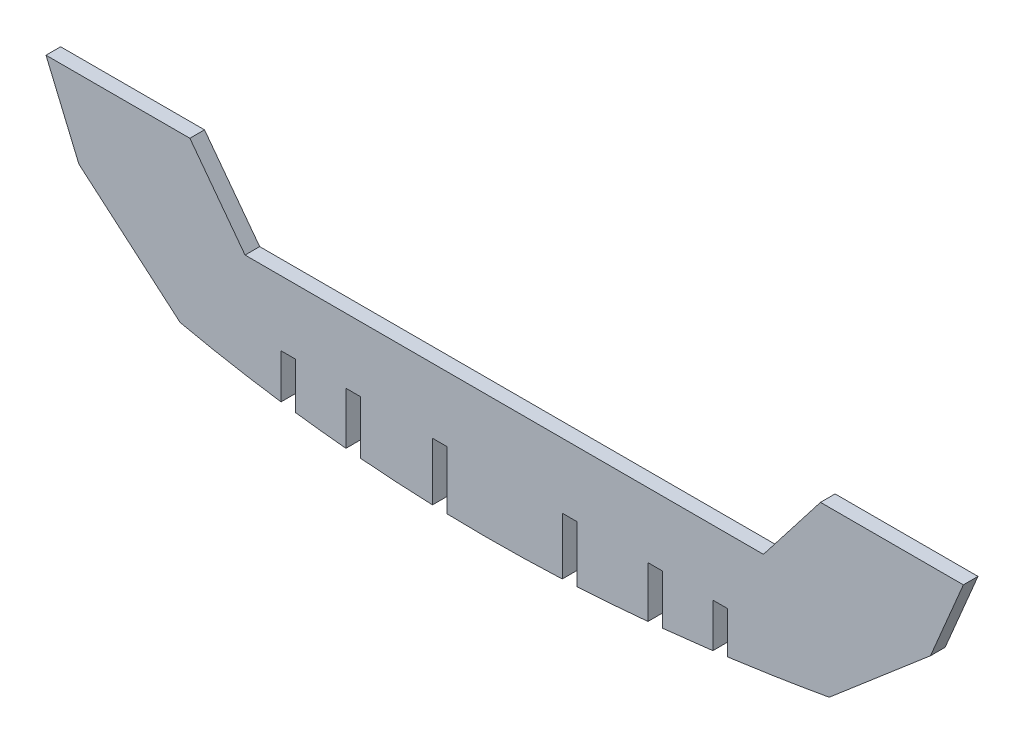
SolidWorks part; units mm, degrees
ref_plane "Front Plane" through (0, 0, 0) normal (0, 0, 1) x (1, 0, 0)
ref_plane "Top Plane" through (0, 0, 0) normal (0, 1, 0) x (1, 0, 0)
ref_plane "Right Plane" through (0, 0, 0) normal (1, 0, 0) x (0, 0, -1)
sketch "Sketch1" plane through (0, 0, 0) normal (0, 0, 1) x (1, 0, 0)
  line L0 (-76.2, 19.05) -> (-83.82, 29.21)
  line L1 (-83.82, 29.21) -> (-134.62, 29.21)
  line L2 (-76.2, -19.05) -> (-95.25, -19.05)
  line L3 (-76.2, 19.05) -> (76.2, 19.05)
  line L4 (-76.2, 19.05) -> (-76.2, -19.05)
  line L5 (-76.2, -19.05) -> (76.2, -19.05)
  line L6 (76.2, 19.05) -> (76.2, -19.05)
  line L7 (-76.2, 19.05) -> (76.2, -19.05) construction
  line L8 (-76.2, -19.05) -> (76.2, 19.05) construction
  line L9 (-95.25, -19.05) -> (-124.968, 6.35)
  line L10 (76.2, 19.05) -> (83.82, 29.21)
  line L11 (83.82, 29.21) -> (134.62, 29.21)
  line L12 (134.62, 29.21) -> (124.968, 6.35)
  line L13 (124.968, 6.35) -> (95.25, -19.05)
  line L14 (95.25, -19.05) -> (76.2, -19.05)
  spline S0 degree 1 poles (-134.62, 29.21) (-124.968, 6.35) knots 0 0 1 1
  spline S1 degree 3 poles (-95.25, -19.05) (-66.0792, -25.5147) (-2.1216, -32.0837) (61.7619, -25.0102) (95.25, -19.05) knots 0 0 0 0 0.467199 1 1 1 1
  point P4 (0, 0)
  dimension "D1" = 152.4
  dimension "D2" = 38.1
  dimension "D3" = 12.7
  dimension "D4" = 50.8
  dimension "D5" = 12.7
  dimension "D6" = 19.05
  dimension "D7" = 19.05
  dimension "D8" = 50.8
  dimension "D9" = 48.26
  dimension "D10" = 48.26
  dimension "D11" = 25.4
  dimension "D12" = 48.768
  dimension "D13" = 48.768
extrude "Boss-Extrude1" add sketch "Sketch1" along normal blind 4.2926 contours L1 S0 L9 L2 L4 L0 | L6 L3 L4 L5 | L2 S1 L14 L5 | L14 L13 L12 L11 L10 L6
sketch "Sketch2" plane through (0, 0, 4.2926) normal (0, 0, 1) x (1, 0, 0)
  line L1 (-76.2, 19.05) -> (75.9425, 19.05)
  line L2 (-76.2, 19.05) -> (-76.2, 7.62)
  line L3 (-76.2, 7.62) -> (75.9425, 7.62)
  line L4 (75.9425, 19.05) -> (75.9425, 7.62)
  dimension "D1" = 11.43
extrude "Cut-Extrude1" cut sketch "Sketch2" against normal blind 4.2926
sketch "Sketch3" plane through (0, 0, 4.2926) normal (0, 0, 1) x (1, 0, 0)
  line L1 (-65.6463, -31.75) -> (-61.3537, -31.75)
  line L2 (-65.6463, -31.75) -> (-65.6463, -11.43)
  line L3 (-65.6463, -11.43) -> (-61.3537, -11.43)
  line L4 (-61.3537, -31.75) -> (-61.3537, -11.43)
  line L5 (-65.6463, -31.75) -> (-61.3537, -11.43) construction
  line L6 (-65.6463, -11.43) -> (-61.3537, -31.75) construction
  line L7 (-46.5963, -31.75) -> (-42.3037, -31.75)
  line L8 (-46.5963, -31.75) -> (-46.5963, -11.43)
  line L9 (-46.5963, -11.43) -> (-42.3037, -11.43)
  line L10 (-42.3037, -31.75) -> (-42.3037, -11.43)
  line L11 (-46.5963, -31.75) -> (-42.3037, -11.43) construction
  line L12 (-46.5963, -11.43) -> (-42.3037, -31.75) construction
  line L13 (-21.1963, -11.43) -> (-16.9037, -11.43)
  line L14 (-21.1963, -11.43) -> (-21.1963, -31.75)
  line L15 (-21.1963, -31.75) -> (-16.9037, -31.75)
  line L16 (-16.9037, -11.43) -> (-16.9037, -31.75)
  line L17 (-21.1963, -11.43) -> (-16.9037, -31.75) construction
  line L18 (-21.1963, -31.75) -> (-16.9037, -11.43) construction
  line L19 (42.0462, -11.43) -> (46.3388, -11.43)
  line L20 (42.0462, -11.43) -> (42.0462, -31.75)
  line L21 (42.0462, -31.75) -> (46.3388, -31.75)
  line L22 (46.3388, -11.43) -> (46.3388, -31.75)
  line L23 (42.0462, -11.43) -> (46.3388, -31.75) construction
  line L24 (42.0462, -31.75) -> (46.3388, -11.43) construction
  line L25 (61.0962, -11.43) -> (65.3888, -11.43)
  line L26 (61.0962, -11.43) -> (61.0962, -31.75)
  line L27 (61.0962, -31.75) -> (65.3888, -31.75)
  line L28 (65.3888, -11.43) -> (65.3888, -31.75)
  line L29 (61.0962, -11.43) -> (65.3888, -31.75) construction
  line L30 (61.0962, -31.75) -> (65.3888, -11.43) construction
  line L33 (-76.2, 7.62) -> (75.9425, 7.62) construction
  line L34 (16.9037, -11.43) -> (21.1963, -11.43)
  line L35 (16.9037, -11.43) -> (16.9037, -31.75)
  line L36 (16.9037, -31.75) -> (21.1963, -31.75)
  line L37 (21.1963, -11.43) -> (21.1963, -31.75)
  line L38 (16.9037, -11.43) -> (21.1963, -31.75) construction
  line L39 (16.9037, -31.75) -> (21.1963, -11.43) construction
  line L40 (-76.2, 19.05) -> (-76.2, 7.62) construction
  line L41 (75.9425, 7.62) -> (75.9425, 19.05) construction
  line L42 (-92.3925, 29.21) -> (-76.2, 7.62)
  line L43 (-83.82, 29.21) -> (-134.62, 29.21) construction
  line L44 (-76.2, 19.05) -> (-83.82, 29.21) construction
  line L45 (-92.3925, 29.21) -> (-83.82, 29.21)
  line L46 (-83.82, 29.21) -> (-76.2, 19.05)
  line L47 (-76.2, 19.05) -> (-76.2, 7.62)
  line L48 (75.9425, 7.62) -> (92.6822, 29.21)
  line L49 (83.82, 29.21) -> (134.62, 29.21) construction
  line L50 (92.6822, 29.21) -> (83.82, 29.21)
  line L51 (83.82, 29.21) -> (75.9425, 19.05)
  line L52 (75.9425, 19.05) -> (75.9425, 7.62)
  point P0 (-63.5, -21.59)
  point P5 (-44.45, -21.59)
  point P10 (-19.05, -21.59)
  point P15 (44.1925, -21.59)
  point P20 (63.2425, -21.59)
  point P33 (19.05, -21.59)
  dimension "D1" = 4.2926
  dimension "D2" = 4.2926
  dimension "D3" = 4.2926
  dimension "D4" = 4.2926
  dimension "D5" = 4.2926
  dimension "D8" = 4.2926
  dimension "D9" = 19.05
  dimension "D10" = 19.05
  dimension "D6" = 12.7
  dimension "D7" = 12.7
  dimension "D11" = 19.05
  dimension "D12" = 19.05
  dimension "D13" = 19.05
  dimension "D14" = 31.75
extrude "Cut-Extrude2" cut sketch "Sketch3" against normal blind 4.2926
equation "\"thick\"=0.169"
equation "\"D1@Cut-Extrude1\"=\"thick\""
equation "\"D1@Sketch3\"=\"thick\""
equation "\"D2@Sketch3\"=\"thick\""
equation "\"D3@Sketch3\"=\"thick\""
equation "\"D4@Sketch3\"=\"thick\""
equation "\"D5@Sketch3\"=\"thick\""
equation "\"D8@Sketch3\"=\"thick\""
